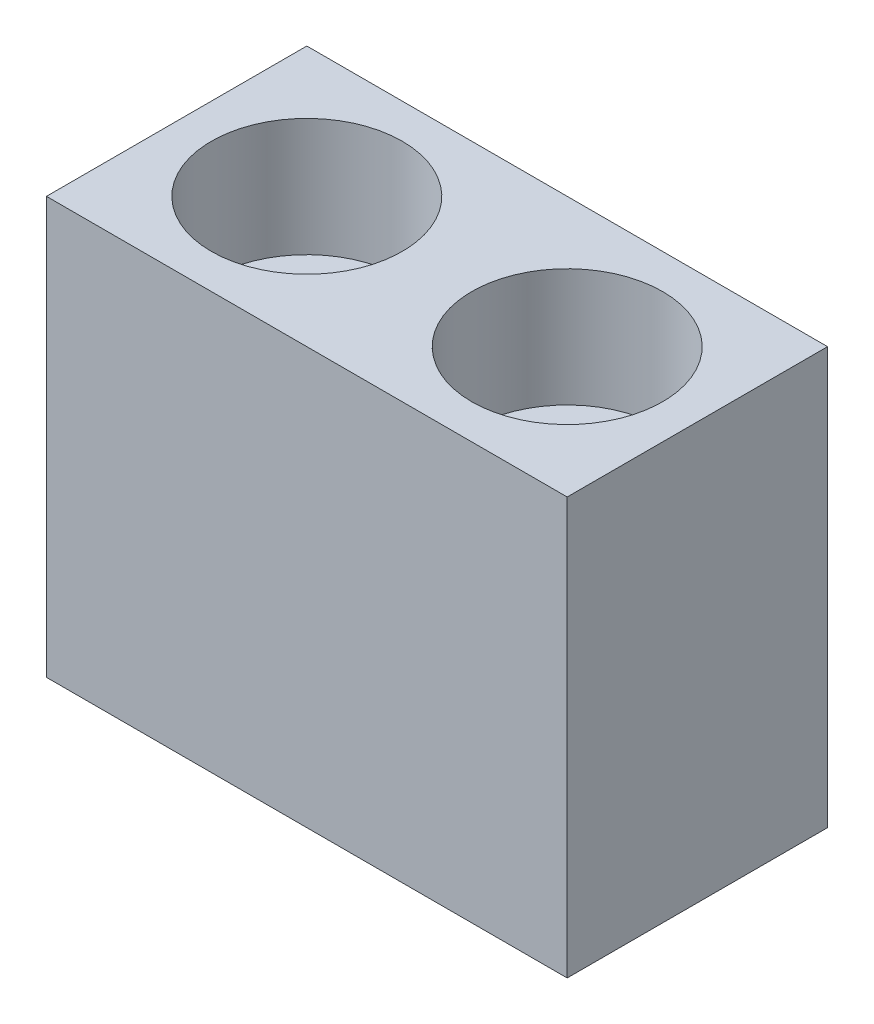
SolidWorks part; units mm, degrees
material "6061"
ref_plane "前视" through (0, 0, 0) normal (0, 0, 1) x (1, 0, 0)
ref_plane "上视" through (0, 0, 0) normal (0, 1, 0) x (1, 0, 0)
ref_plane "右视" through (0, 0, 0) normal (1, 0, 0) x (0, 0, -1)
sketch "草图1" plane through (0, 0, 0) normal (0, 1, 0) x (1, 0, 0)
  line L1 (-15, -7.5) -> (15, -7.5)
  line L2 (-15, -7.5) -> (-15, 7.5)
  line L3 (-15, 7.5) -> (15, 7.5)
  line L4 (15, -7.5) -> (15, 7.5)
  line L5 (-15, -7.5) -> (15, 7.5) construction
  line L6 (-15, 7.5) -> (15, -7.5) construction
  point P0 (0, 0)
  dimension "D1" = 30
  dimension "D2" = 15
extrude "凸台-拉伸1" add sketch "草图1" along normal blind 24
hole_wizard "打孔尺寸根据内六角圆柱头螺钉的类型1" positions "草图3" profile "草图2" counterbore size "M6" standard "Gb" end condition through all
sketch "草图3" plane through (0, 24, 0) normal (0, 1, 0) x (1, 0, 0)
  line L0 (-15, 0) -> (0, 0) construction
  line L1 (-15, 7.5) -> (-15, -7.5) construction
  line L2 (0, 0) -> (0, 7.5) construction
  line L3 (15, 7.5) -> (-15, 7.5) construction
  point P0 (-7.5, 0)
  point P14 (7.5, 0)
  dimension "D1" = 15
sketch "草图2" plane through (-7.5, 24, 0) normal (1, 0, 0) x (0, 0, 1)
  line L0 (0, 0) -> (0, 24)
  line L1 (0, 24) -> (3.3, 24)
  line L3 (3.3, 24) -> (3.3, 6.8)
  line L4 (3.3, 6.8) -> (5.5, 6.8)
  line L5 (5.5, 6.8) -> (5.5, 0)
  line L7 (5.5, 0) -> (0, 0)
  line L11 (0, -6.35) -> (0, 107.95) construction
  dimension "通孔孔直径" = 6.6
  dimension "通孔孔深度" = 24
  dimension "柱形沉头孔直径" = 11
  dimension "柱形沉头孔深度" = 6.8
